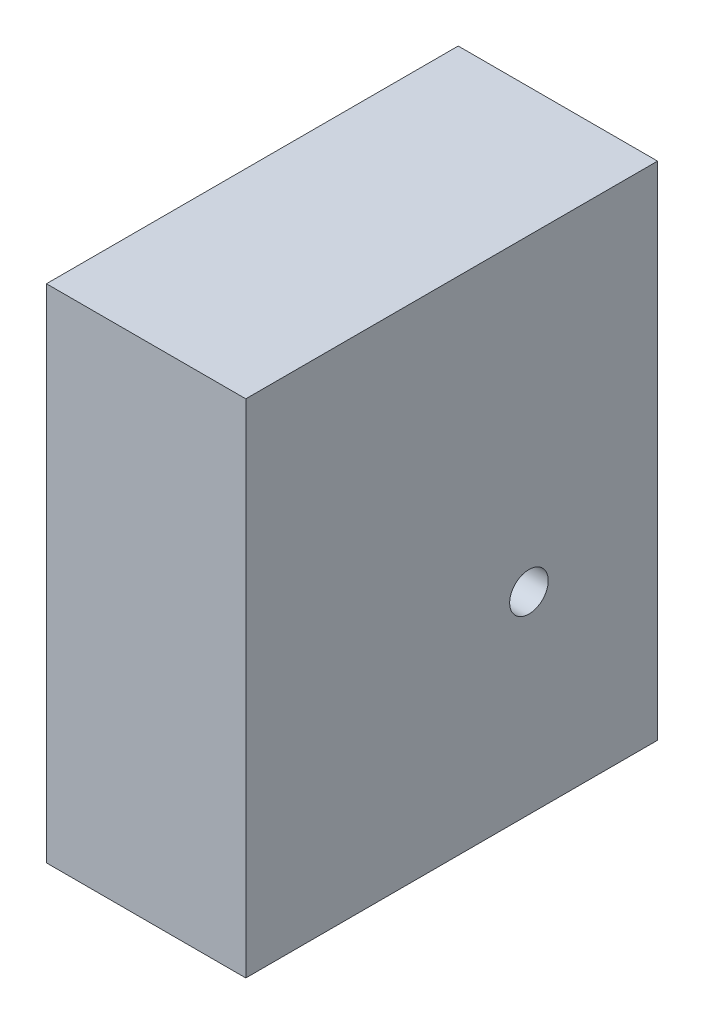
SolidWorks part; units mm, degrees
material "Balsa"
ref_plane "Front Plane" through (0, 0, 0) normal (0, 0, 1) x (1, 0, 0)
ref_plane "Top Plane" through (0, 0, 0) normal (0, 1, 0) x (1, 0, 0)
ref_plane "Right Plane" through (0, 0, 0) normal (1, 0, 0) x (0, 0, -1)
sketch "Sketch1" plane through (0, 0, 0) normal (0, 0, 1) x (1, 0, 0)
  line L1 (-77.5, 195) -> (77.5, 195)
  line L2 (-77.5, 195) -> (-77.5, -195)
  line L3 (-77.5, -195) -> (77.5, -195)
  line L4 (77.5, 195) -> (77.5, -195)
  line L5 (-77.5, 195) -> (77.5, -195) construction
  line L6 (-77.5, -195) -> (77.5, 195) construction
  point P0 (0, 0)
  dimension "D1" = 390
  dimension "D2" = 155
extrude "Boss-Extrude1" add sketch "Sketch1" along normal blind 320.16
sketch "Sketch2" plane through (0, 0, 0) normal (0, 0, -1) x (-1, 0, 0)
  line L0 (-77.5, 5) -> (-50, 5) construction
  line L1 (-50, 5) -> (50, 5)
  line L2 (-50, 5) -> (-50, -95)
  line L3 (-50, -95) -> (50, -95)
  line L4 (50, 5) -> (50, -95)
  line L5 (-50, 5) -> (50, -95) construction
  line L6 (-50, -95) -> (50, 5) construction
  line L7 (50, 5) -> (77.5, 5) construction
  line L8 (77.5, 195) -> (77.5, -195) construction
  line L9 (-77.5, -195) -> (-77.5, 195) construction
  line L10 (0, -95) -> (0, -195) construction
  line L11 (77.5, -195) -> (-77.5, -195) construction
  point P0 (0, -45)
  point P6 (0, 0)
  point P9 (0, 0)
  point P16 (0, 0)
  dimension "D1" = 100
  dimension "D2" = 100
extrude "Cut-Extrude1" cut sketch "Sketch2" against normal blind 150
sketch "Sketch3" plane through (77.5, 0, 0) normal (1, 0, 0) x (0, 0, -1)
  line L0 (-100, -45) -> (0, -45) construction
  line L1 (-100, -45) -> (-100, -195) construction
  line L2 (0, -95) -> (0, 5) construction
  line L3 (-320.16, -195) -> (0, -195) construction
  circle A0 centre (-100, -45) radius 15
  point P0 (-69.5356, -36.0845)
  point P6 (0, 0)
  dimension "D2" = 30
  dimension "D1" = 100
extrude "Cut-Extrude2" cut sketch "Sketch3" against normal through all both and the other way through all
